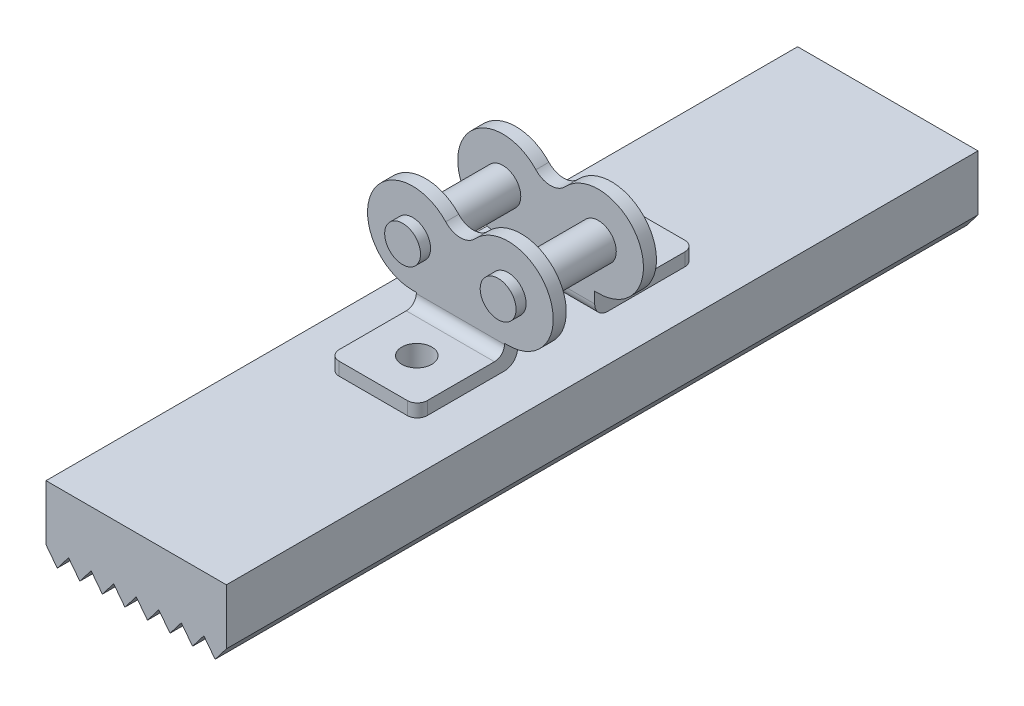
SolidWorks part; units mm, degrees
ref_plane "Alzado" through (0, 0, 0) normal (0, 0, 1) x (1, 0, 0)
ref_plane "Planta" through (0, 0, 0) normal (0, 1, 0) x (1, 0, 0)
ref_plane "Vista lateral" through (0, 0, 0) normal (1, 0, 0) x (0, 0, -1)
sketch "Sketch1" plane through (0, 0, 0) normal (0, 0, 1) x (1, 0, 0)
  line L0 (-9.265, 0) -> (9.265, 0) construction
  line L1 (0, 10.9987) -> (0, -12.9647) construction
  line L2 (-4.765, -4.5) -> (4.765, -4.5)
  arc A0 (-1.4662, 3.0607) -> (-4.765, -4.5) centre (-4.765, 0) ccw
  arc A1 (-1.4662, 3.0607) -> (1.4662, 3.0607) centre (0, 4.4209) ccw
  arc A2 (1.4662, 3.0607) -> (4.765, -4.5) centre (4.765, 0) cw
  point P4 (0, 0)
  point P15 (0, -4.5)
  dimension "D1" = 9
  dimension "D3" = 2
  dimension "D2" = 9.53
extrude "Boss-Extrude1" add sketch "Sketch1" along normal blind 1.3
sketch "Sketch2" plane through (0, 0, 1.3) normal (0, 0, 1) x (1, 0, 0)
  circle A0 centre (-4.765, 0) radius 1.79
  circle A1 centre (4.765, 0) radius 1.79
  dimension "D1" = 3.58
extrude "Boss-Extrude2" add sketch "Sketch2" against normal blind 2.3 and the other way blind 10
ref_plane "Plane1" through (0, 0, 5.15) normal (0, 0, -1) x (-1, 0, 0)
sketch "Sketch4" plane through (0, -4.5, 0) normal (0, -1, 0) x (1, 0, 0)
  line L0 (-4.765, 1.3) -> (4.765, 1.3) construction
  line L1 (-4.4, 1.3) -> (4.4, 1.3)
  line L2 (-4.4, 1.3) -> (-4.4, 0)
  line L3 (-4.4, 0) -> (4.4, 0)
  line L4 (4.4, 1.3) -> (4.4, 0)
  line L5 (2.975, 0) -> (6.555, 0) construction
  point P8 (0, 1.3)
  dimension "D1" = 8.8
extrude "Boss-Extrude4" add sketch "Sketch4" along normal blind 2.4
sketch "Sketch3" plane through (0, -6.9, 0) normal (0, -1, 0) x (1, 0, 0)
  line L0 (-4.765, 1.3) -> (-4.4, 1.3) construction
  line L1 (-4.4, 1.3) -> (4.4, 1.3)
  line L2 (-4.4, 1.3) -> (-4.4, -8.7)
  line L3 (-4.4, -8.7) -> (4.4, -8.7)
  line L4 (4.4, 1.3) -> (4.4, -8.7)
  point P6 (0, 1.3)
  dimension "D1" = 8.8
  dimension "D2" = 10
extrude "Boss-Extrude3" add sketch "Sketch3" against normal blind 1.3
fillet "Fillet4" radius 1.3 1 edges at (0, -6.9, 1.3)
fillet "Fillet6" radius 1 1 edges at (0, -5.6, 0)
sketch "Sketch5" plane through (0, -6.9, 0) normal (0, -1, 0) x (1, 0, 0)
  line L0 (-4.4, 0) -> (4.4, -8.7) construction
  line L1 (-4.4, -8.7) -> (4.4, 0) construction
  circle A0 centre (0, -4.35) radius 1.5
  dimension "D1" = 3
extrude "Cut-Extrude1" cut sketch "Sketch5" against normal blind 2.4
fillet "Fillet7" radius 1 2 edges at (4.4, -6.25, -8.7) (-4.4, -6.25, -8.7)
mirror "Mirror1" about plane through (0, 0, 5.15) normal (0, 0, -1) of "Fillet7", "Cut-Extrude1", "Fillet6", "Fillet4", "Boss-Extrude4", "Boss-Extrude1", "Boss-Extrude3"
sketch "Sketch6" plane through (0, -6.9, 0) normal (0, -1, 0) x (1, 0, 0)
  line L0 (0, 19) -> (0, -8.7) construction
  line L1 (-3.4, 19) -> (3.4, 19) construction
  line L2 (-3.4, -8.7) -> (3.4, -8.7) construction
  line L4 (-9, 42.65) -> (9, 42.65)
  line L5 (-9, 42.65) -> (-9, -32.35)
  line L6 (-9, -32.35) -> (9, -32.35)
  line L7 (9, 42.65) -> (9, -32.35)
  line L8 (-9, 42.65) -> (9, -32.35) construction
  line L9 (-9, -32.35) -> (9, 42.65) construction
  circle A0 centre (0, 14.65) radius 1.5 construction
  circle A1 centre (0, -4.35) radius 1.5 construction
  circle A2 centre (0, 14.65) radius 1.5
  circle A3 centre (0, -4.35) radius 1.5
  point P12 (0, 5.15)
  dimension "D1" = 18
  dimension "D2" = 75
extrude "Boss-Extrude5" add sketch "Sketch6" along normal blind 7
sketch "Sketch9" plane through (0, -13.9, 0) normal (0, -1, 0) x (1, 0, 0)
  circle A0 centre (0, 14.65) radius 4
  circle A1 centre (0, -4.35) radius 4
  dimension "D1" = 8
extrude "Cut-Extrude3" cut sketch "Sketch9" against normal blind 3
sketch "Sketch11" plane through (0, 0, 42.65) normal (0, 0, 1) x (1, 0, 0)
  line L1 (-9, -13.9) -> (-9, -6.9) construction
  line L2 (9, -13.9) -> (9, -6.9) construction
  line L3 (9, -13.9) -> (-9, -13.9) construction
  line L4 (9, -12.433) -> (7.875, -13.9)
  line L5 (7.875, -13.9) -> (6.75, -12.433)
  line L6 (5.625, -13.9) -> (4.5, -12.433)
  line L7 (6.75, -12.433) -> (5.625, -13.9)
  line L8 (3.375, -13.9) -> (2.25, -12.433)
  line L9 (4.5, -12.433) -> (3.375, -13.9)
  line L10 (1.125, -13.9) -> (0, -12.433)
  line L11 (2.25, -12.433) -> (1.125, -13.9)
  line L12 (-1.125, -13.9) -> (-2.25, -12.433)
  line L13 (0, -12.433) -> (-1.125, -13.9)
  line L14 (-3.375, -13.9) -> (-4.5, -12.433)
  line L15 (-2.25, -12.433) -> (-3.375, -13.9)
  line L16 (-5.625, -13.9) -> (-6.75, -12.433)
  line L17 (-4.5, -12.433) -> (-5.625, -13.9)
  line L18 (-7.875, -13.9) -> (-9, -12.433)
  line L19 (-6.75, -12.433) -> (-7.875, -13.9)
  line L22 (-9, -12.433) -> (-9, -14.9)
  line L23 (-9, -14.9) -> (9, -14.9)
  line L24 (9, -12.433) -> (9, -14.9)
  dimension "D1" = 1
  dimension "D2" = 2.25
  dimension "D3" = 1.125
  dimension "D4" = 8
extrude "Cut-Extrude4" cut sketch "Sketch11" against normal through all
